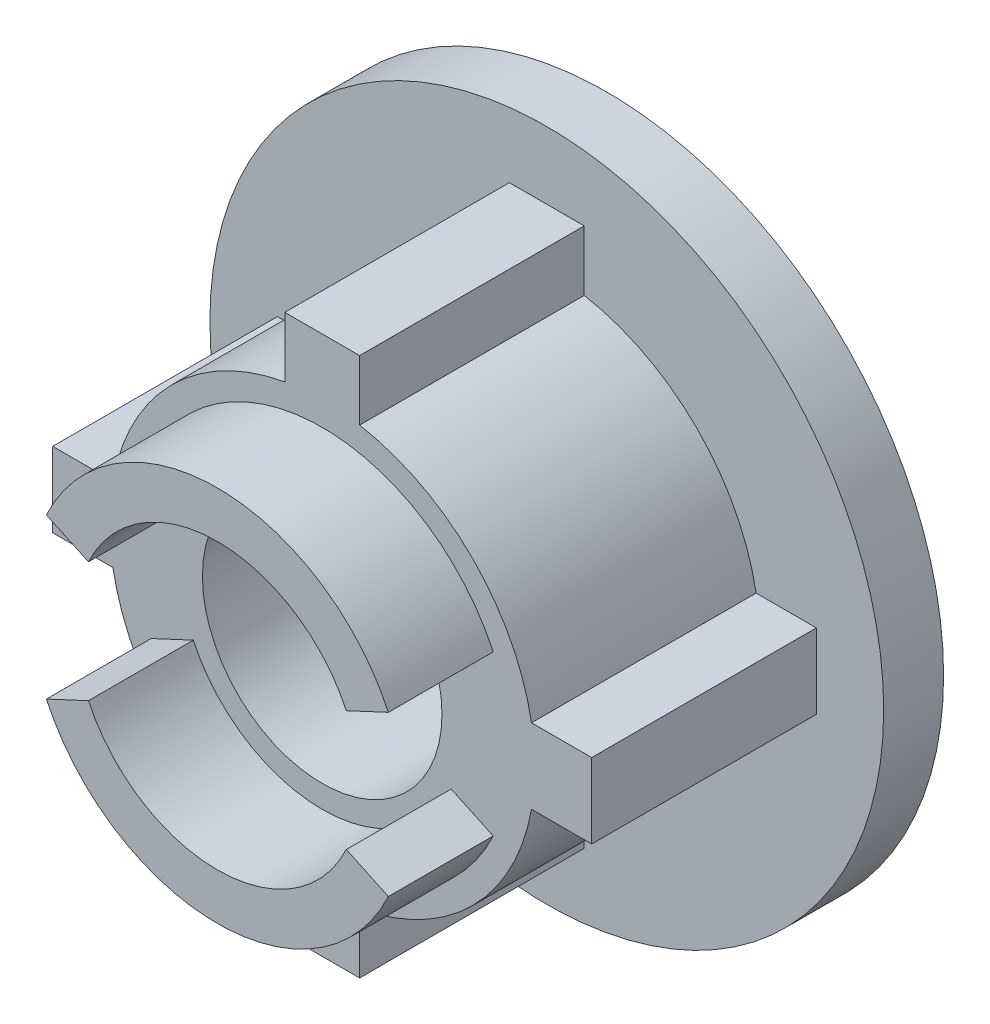
SolidWorks part; units mm, degrees
ref_plane "Plano frontal" through (0, 0, 0) normal (0, 0, 1) x (1, 0, 0)
ref_plane "Plano superior" through (0, 0, 0) normal (0, 1, 0) x (1, 0, 0)
ref_plane "Plano direito" through (0, 0, 0) normal (1, 0, 0) x (0, 0, -1)
sketch "Esboço1" plane through (0, 0, 0) normal (0, 0, 1) x (1, 0, 0)
  line L0 (18, 2.5) -> (13.9782, 2.5)
  line L1 (18, -2.5) -> (18, 2.5)
  line L2 (13.9782, -2.5) -> (18, -2.5)
  line L3 (2.5, -18) -> (2.5, -13.9782)
  line L4 (-2.5, -18) -> (2.5, -18)
  line L5 (-2.5, -13.9782) -> (-2.5, -18)
  line L6 (-18, -2.5) -> (-13.9782, -2.5)
  line L7 (-18, 2.5) -> (-18, -2.5)
  line L8 (-13.9782, 2.5) -> (-18, 2.5)
  line L9 (-2.5, 18) -> (-2.5, 13.9782)
  line L10 (2.5, 18) -> (-2.5, 18)
  line L11 (2.5, 13.9782) -> (2.5, 18)
  circle A0 centre (0, 0) radius 11.15
  circle A1 centre (0, 0) radius 6.1
  circle A3 centre (0, 0) radius 4.3
  arc A4 (-13.9782, -2.5) -> (-2.5, -13.9782) centre (0, 0) ccw
  arc A5 (13.9782, 2.5) -> (2.5, 13.9782) centre (0, 0) ccw
  arc A6 (2.5, -13.9782) -> (13.9782, -2.5) centre (0, 0) ccw
  arc A7 (-13.9782, -2.5) -> (-2.5, -13.9782) centre (0, 0) ccw
  arc A8 (-2.5, 13.9782) -> (-13.9782, 2.5) centre (0, 0) ccw
  arc A9 (-2.5, 13.9782) -> (-13.9782, 2.5) centre (0, 0) ccw
  arc A10 (13.9782, 2.5) -> (2.5, 13.9782) centre (0, 0) ccw
  arc A11 (2.5, -13.9782) -> (13.9782, -2.5) centre (0, 0) ccw
  dimension "D1" = 28.4
  dimension "D2" = 8.6
  dimension "D3" = 12.2
  dimension "D5" = 22.3
  dimension "D6" = 14.2
  dimension "D7" = 14.2
  dimension "D8" = 14.2
  dimension "D9" = 14.2
  dimension "D10" = 2.5
  dimension "D11" = 2.5
  dimension "D12" = 13.9782
  dimension "D13" = 13.9782
  dimension "D14" = 18
  dimension "D15" = 18
  dimension "D16" = 2.5
  dimension "D17" = 2.5
  dimension "D18" = 13.9782
  dimension "D19" = 13.9782
  dimension "D20" = 18
  dimension "D21" = 18
  dimension "D22" = 2.5
  dimension "D23" = 2.5
  dimension "D24" = 13.9782
  dimension "D25" = 13.9782
  dimension "D26" = 18
  dimension "D27" = 18
  dimension "D28" = 2.5
  dimension "D29" = 2.5
  dimension "D30" = 13.9782
  dimension "D31" = 13.9782
  dimension "D32" = 18
  dimension "D33" = 18
extrude "Ressalto-extrusão1" add sketch "Esboço1" along normal blind 15 contours L9 A8 L8 L7 L6 A4 L5 L4 L3 A6 L2 L1 L0 A5 L11 L10 A0
sketch "Esboço2" plane through (0, 0, 0) normal (0, 0, -1) x (-1, 0, 0)
  line L4 (2.5, 18) -> (2.5, 13.9782) construction
  line L5 (-2.5, 18) -> (2.5, 18) construction
  circle A0 centre (0, 0) radius 22.5
  arc A9 (2.5, 13.9782) -> (-13.9782, -2.5) centre (0, 0) ccw
  arc A10 (-13.9782, -2.5) -> (2.5, -13.9782) centre (0, 0) ccw
  arc A11 (-2.5, -13.9782) -> (13.9782, -2.5) centre (0, 0) ccw
  arc A12 (13.9782, -2.5) -> (2.5, 13.9782) centre (0, 0) ccw
  line M18 (2.5, 13.9782) -> (2.5, 18)
  line M19 (2.5, 18) -> (-2.5, 18)
  line M20 (-2.5, 18) -> (-2.5, 13.9782)
  arc M21 (-2.5, 13.9782) -> (-13.9782, 2.5) centre (0, 0) ccw
  line M22 (-13.9782, 2.5) -> (-18, 2.5)
  line M23 (-18, 2.5) -> (-18, -2.5)
  line M24 (-18, -2.5) -> (-13.9782, -2.5)
  arc M25 (-13.9782, -2.5) -> (-2.5, -13.9782) centre (0, 0) ccw
  line M26 (-2.5, -13.9782) -> (-2.5, -18)
  line M27 (-2.5, -18) -> (2.5, -18)
  line M28 (2.5, -18) -> (2.5, -13.9782)
  arc M29 (2.5, -13.9782) -> (13.9782, -2.5) centre (0, 0) ccw
  line M30 (13.9782, -2.5) -> (18, -2.5)
  line M31 (18, -2.5) -> (18, 2.5)
  line M32 (18, 2.5) -> (13.9782, 2.5)
  arc M33 (13.9782, 2.5) -> (2.5, 13.9782) centre (0, 0) ccw
  dimension "D1" = 45
  dimension "D2" = 14.2
  dimension "D3" = 14.2
  dimension "D4" = 14.2
  dimension "D5" = 14.2
  dimension "D6" = 11.4782
  dimension "D7" = 2.5
  dimension "D8" = 5
  dimension "D9" = 16.4782
  dimension "D10" = 4.0218
  dimension "D11" = 18
  dimension "D12" = 31.9782
  dimension "D14" = 20.5
  dimension "D15" = 20.5
  dimension "D16" = 31.9782
extrude "Ressalto-extrusão2" add sketch "Esboço2" along normal blind 4 separate body contours A0 M18 M33 M32 M31 M30 M29 M28 M27 M26 M25 M24 M23 M22 M21 M20 M19 | A10 M26 M27 M28 | A9 M22 M23 M24 | A9 M18 M19 M20 | A12 M30 M31 M32
sketch "Esboço5" plane through (0, 0, 15) normal (0, 0, 1) x (1, 0, 0)
  circle A0 centre (0, 0) radius 11.15 construction
  circle A1 centre (0, 0) radius 11.15
  circle A2 centre (0, 0) radius 8
  dimension "D1" = 16
extrude "Ressalto-extrusão6" add sketch "Esboço5" against normal blind 8
sketch "Esboço7" plane through (0, 0, 0) normal (0, 0, -1) x (-1, 0, 0)
  circle A0 centre (0, 0) radius 11.15 construction
  circle A1 centre (0, 0) radius 14.2 construction
  circle A2 centre (0, 0) radius 11.15
  circle A3 centre (0, 0) radius 14.2
extrude "Ressalto-extrusão7" add sketch "Esboço7" along normal up to surface (4 mm away) up to face at (-14.2, 0, -4)
sketch "Esboço8" plane through (0, 0, 7) normal (0, 0, -1) x (-1, 0, 0)
  circle A0 centre (0, 0) radius 8 construction
  circle A1 centre (0, 0) radius 11.15 construction
  circle A2 centre (0, 0) radius 8
  circle A3 centre (0, 0) radius 11.15
extrude "Ressalto-extrusão8" add sketch "Esboço8" along normal blind 4
sketch "Esboço9" plane through (0, 0, 15) normal (0, 0, 1) x (1, 0, 0)
  line L0 (2.5, -18) -> (2.5, -13.9782) construction
  line L1 (-2.5, -18) -> (2.5, -18) construction
  line L2 (-11.4195, 5.325) -> (-8.6099, 4.0149)
  line L4 (-11.4195, -5.325) -> (-8.6099, -4.0149)
  line L7 (8.6099, -4.0149) -> (11.4195, -5.325)
  line L8 (8.6099, 4.0149) -> (11.4195, 5.325)
  arc A0 (-8.6099, -4.0149) -> (8.6099, -4.0149) centre (0, 0) ccw
  arc A6 (8.6099, 4.0149) -> (-8.6099, 4.0149) centre (0, 0) ccw
  arc A7 (11.4195, 5.325) -> (-11.4195, 5.325) centre (0, 0) ccw
  arc A15 (-11.4195, -5.325) -> (11.4195, -5.325) centre (0, 0) ccw
  dimension "D2" = 25.2
  dimension "D3" = 2.5
  dimension "D4" = 4.0218
  dimension "D5" = 4.0218
  dimension "D1" = 19
  dimension "D6" = 18
extrude "Ressalto-extrusão9" add sketch "Esboço9" along normal blind 7
